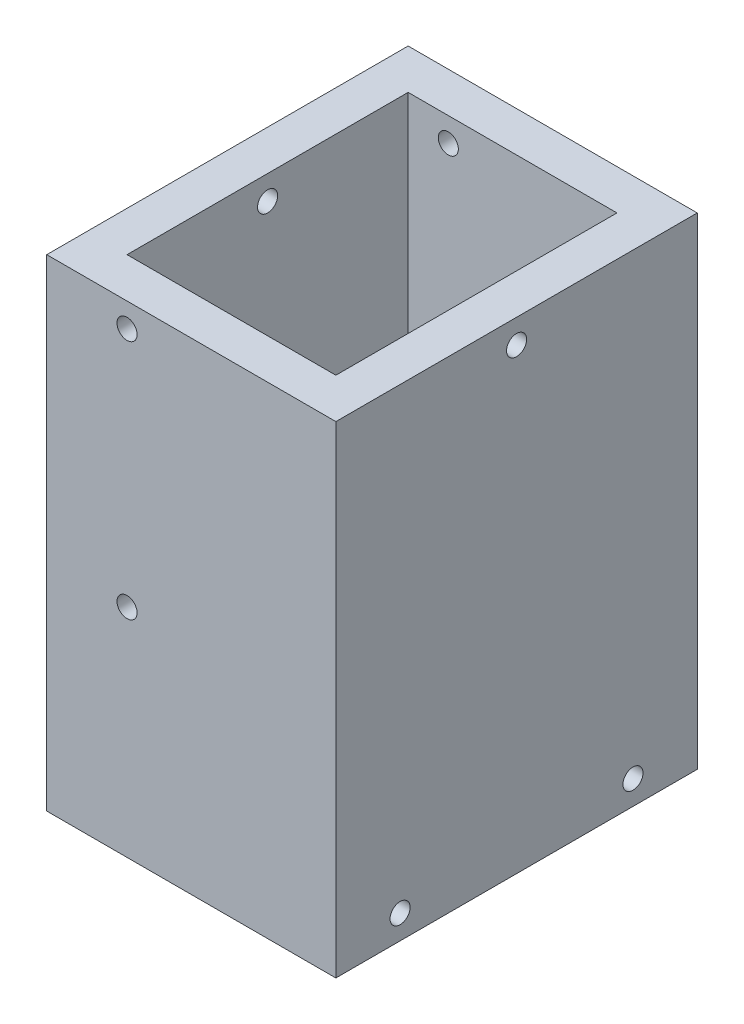
SolidWorks part; units mm, degrees
material "6061 合金"
ref_plane "前视基准面" through (0, 0, 0) normal (0, 0, 1) x (1, 0, 0)
ref_plane "上视基准面" through (0, 0, 0) normal (0, 1, 0) x (1, 0, 0)
ref_plane "右视基准面" through (0, 0, 0) normal (1, 0, 0) x (0, 0, -1)
sketch "草图1" plane through (0, 0, 0) normal (0, 1, 0) x (1, 0, 0)
  line L1 (-13, -17.5) -> (13, -17.5)
  line L2 (-13, -17.5) -> (-13, 17.5)
  line L3 (-13, 17.5) -> (13, 17.5)
  line L4 (13, -17.5) -> (13, 17.5)
  line L5 (-13, -17.5) -> (13, 17.5) construction
  line L6 (-13, 17.5) -> (13, -17.5) construction
  line L7 (-18, 22.5) -> (18, 22.5)
  line L8 (-18, 22.5) -> (-18, -22.5)
  line L9 (-18, -22.5) -> (18, -22.5)
  line L10 (18, 22.5) -> (18, -22.5)
  line L11 (-18, 22.5) -> (18, -22.5) construction
  line L12 (-18, -22.5) -> (18, 22.5) construction
  point P0 (0, 0)
  point P6 (0, 0)
  dimension "D1" = 35
  dimension "D2" = 26
  dimension "D3" = 36
  dimension "D4" = 45
extrude "凸台-拉伸1" add sketch "草图1" along normal blind 60
sketch "草图4" plane through (-18, 0, 0) normal (-1, 0, 0) x (0, 0, 1)
  line L0 (-22.5, 0) -> (22.5, 0) construction
  line L1 (-22.5, 60) -> (-22.5, 0) construction
  line L2 (22.5, 60) -> (22.5, 0) construction
  circle A0 centre (14.5, 3) radius 1.25
  circle A1 centre (-14.5, 3) radius 1.25
  dimension "D1" = 2.5
  dimension "D2" = 2.5
  dimension "D3" = 3
  dimension "D4" = 3
  dimension "D5" = 8
  dimension "D6" = 8
extrude "切除-拉伸1" cut sketch "草图4" against normal through all
sketch "草图5" plane through (0, 0, 22.5) normal (0, 0, 1) x (1, 0, 0)
  line L0 (-18, 60) -> (18, 60) construction
  line L1 (-18, 60) -> (-18, 0) construction
  circle A0 centre (-8, 57) radius 1.25
  circle A1 centre (-8, 27) radius 1.25
  dimension "D1" = 3
  dimension "D2" = 2.5
  dimension "D3" = 10
  dimension "D4" = 2.5
  dimension "D5" = 10
  dimension "D6" = 30
extrude "切除-拉伸2" cut sketch "草图5" against normal through all
sketch "草图6" plane through (18, 0, 0) normal (1, 0, 0) x (0, 0, -1)
  line L0 (-22.5, 60) -> (22.5, 60) construction
  circle A0 centre (0, 57) radius 1.25
  dimension "D1" = 3
  dimension "D2" = 2.5
extrude "切除-拉伸3" cut sketch "草图6" against normal through all
